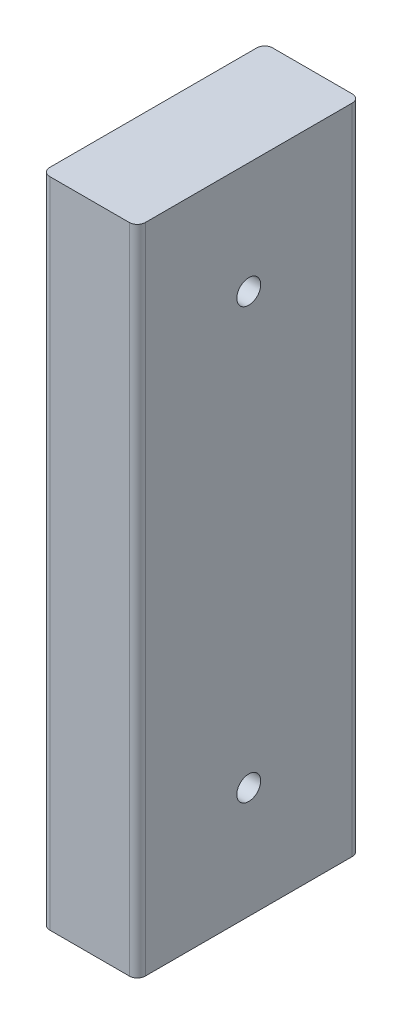
SolidWorks part; units mm, degrees
material "Pine"
ref_plane "Front Plane" through (0, 0, 0) normal (0, 0, 1) x (1, 0, 0)
ref_plane "Top Plane" through (0, 0, 0) normal (0, 1, 0) x (1, 0, 0)
ref_plane "Right Plane" through (0, 0, 0) normal (1, 0, 0) x (0, 0, -1)
sketch "Sketch1" plane through (0, 0, 0) normal (1, 0, 0) x (0, 0, -1)
  line L0 (0, 0) -> (0, 260.35)
  line L1 (0, 260.35) -> (88.9, 260.35)
  line L2 (88.9, 260.35) -> (88.9, 0)
  line L3 (88.9, 0) -> (0, 0)
  dimension "19.75" = 260.35
  dimension "D2" = 88.9
extrude "Boss-Extrude1" add sketch "Sketch1" along normal mid plane 38.1
fillet "Fillet1" radius 3.175 4 edges at (-19.05, 130.175, -88.9) (19.05, 130.175, -88.9) (-19.05, 130.175, 0) (19.05, 130.175, 0)
sketch "Sketch5" plane through (-19.05, 0, 0) normal (-1, 0, 0) x (0, 0, 1)
  line L0 (-44.45, 215.9) -> (-44.45, 44.45) construction
  line L1 (-3.175, 0) -> (-85.725, 0) construction
  line L2 (-88.9, 130.175) -> (-44.45, 130.175) construction
  line L3 (-88.9, 0) -> (-88.9, 260.35) construction
  point P4 (-44.45, 0)
  dimension "D1" = 171.45
hole_wizard "3/8 (0.3750) Dowel Hole1" positions "Sketch6" profile "Sketch7" hole size "3/8" standard "ANSI Inch" end condition up to next
sketch "Sketch6" plane through (-19.05, 0, 0) normal (-1, 0, 0) x (0, 0, 1)
  point P0 (-44.45, 215.9)
  point P5 (-44.45, 44.45)
sketch "Sketch7" plane through (-19.05, 215.9, -44.45) normal (0, 1, 0) x (0, 0, 1)
  line L0 (0, 0) -> (0, 38.1)
  line L1 (0, 38.1) -> (4.7625, 38.1)
  line L2 (4.7625, 38.1) -> (4.7625, 0)
  line L5 (4.7625, 0) -> (0, 0)
  line L11 (0, -6.35) -> (0, 107.95) construction
  dimension "Thru Hole Dia." = 9.525
  dimension "Thru Hole Depth" = 38.1
